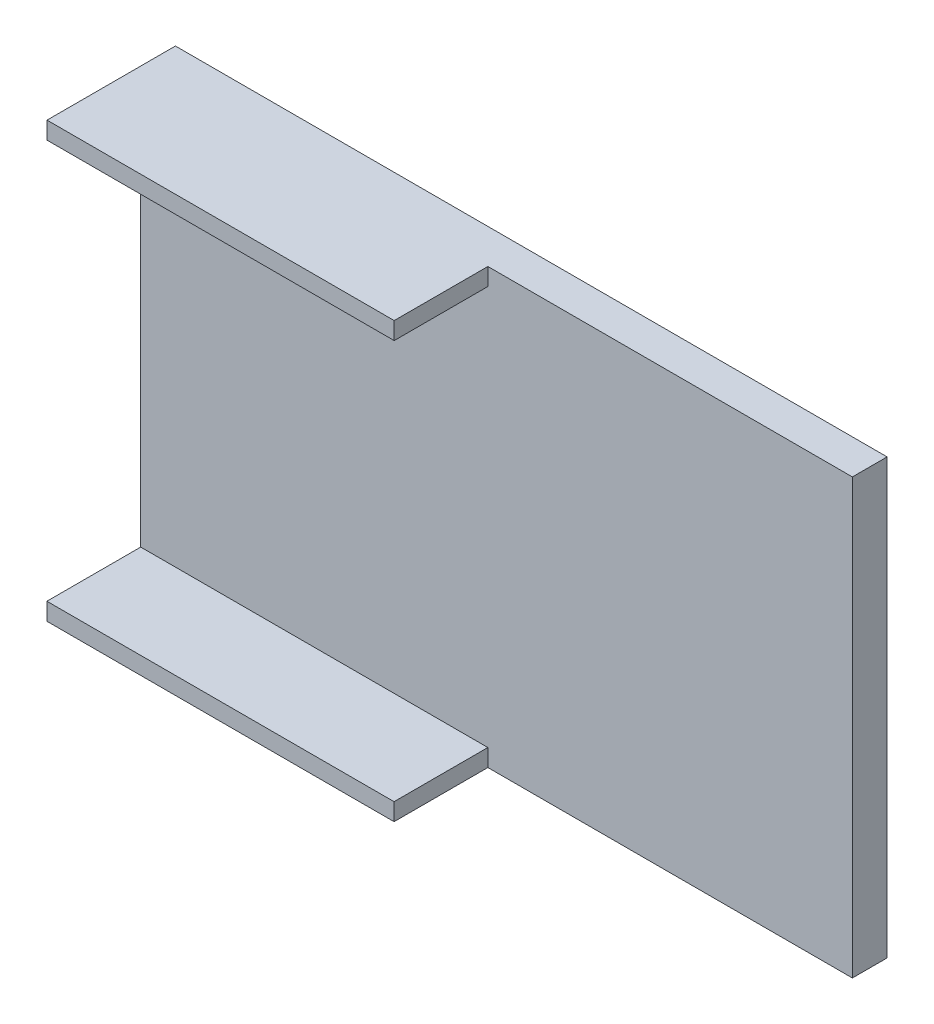
SolidWorks part; units mm, degrees
ref_plane "Plan de face" through (0, 0, 0) normal (0, 0, 1) x (1, 0, 0)
ref_plane "Plan de dessus" through (0, 0, 0) normal (0, 1, 0) x (1, 0, 0)
ref_plane "Plan de droite" through (0, 0, 0) normal (1, 0, 0) x (0, 0, -1)
sketch "Esquisse1" plane through (0, 0, 0) normal (0, 0, 1) x (1, 0, 0)
  line L1 (0.1697, 25.3486) -> (41.1697, 25.3486)
  line L2 (0.1697, 25.3486) -> (0.1697, 0.3486)
  line L3 (0.1697, 0.3486) -> (41.1697, 0.3486)
  line L4 (41.1697, 25.3486) -> (41.1697, 0.3486)
extrude "Boss.-Extru.1" add sketch "Esquisse1" along normal blind 2 contours L2 L3 L4 L1
sketch "Esquisse2" plane through (0, 0, 2) normal (0, 0, 1) x (1, 0, 0)
  line L1 (0.1697, 25.3486) -> (20.1697, 25.3486)
  line L2 (0.1697, 25.3486) -> (0.1697, 24.3486)
  line L3 (0.1697, 24.3486) -> (20.1697, 24.3486)
  line L4 (20.1697, 25.3486) -> (20.1697, 24.3486)
extrude "Boss.-Extru.2" add sketch "Esquisse2" along normal blind 5.3963
sketch "Esquisse3" plane through (0, 0, 2) normal (0, 0, 1) x (1, 0, 0)
  line L5 (0.1697, 0.3486) -> (20.1697, 0.3486)
  line L6 (0.1697, 0.3486) -> (0.1697, 1.3486)
  line L7 (0.1697, 1.3486) -> (20.1697, 1.3486)
  line L8 (20.1697, 0.3486) -> (20.1697, 1.3486)
extrude "Boss.-Extru.3" add sketch "Esquisse3" along normal blind 5.4039
